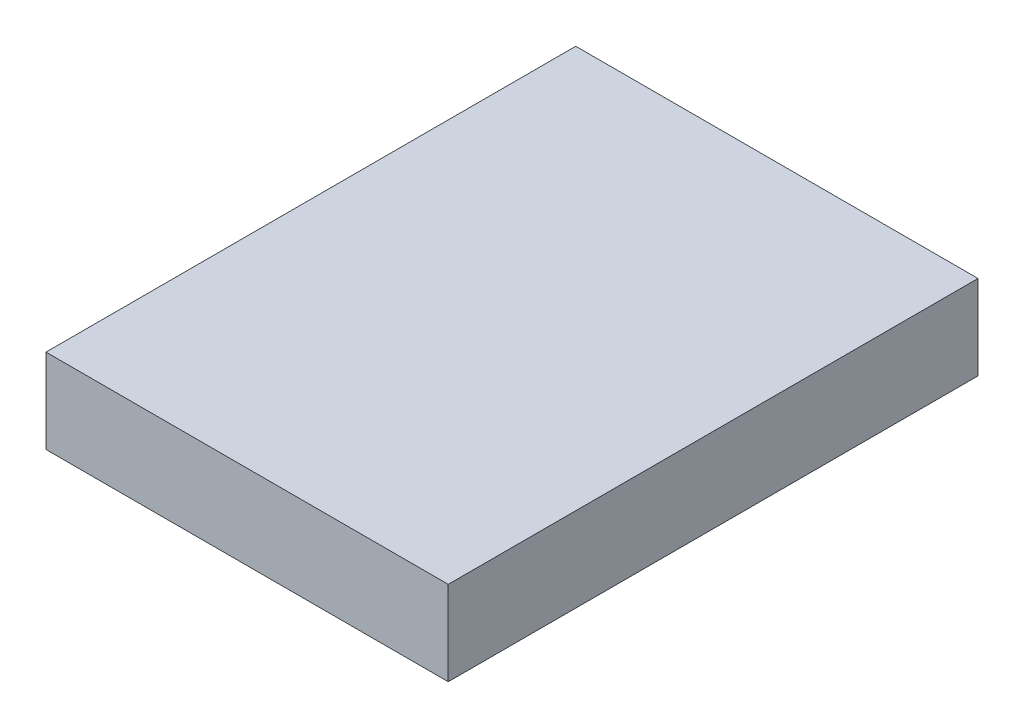
SolidWorks part; units mm, degrees
material "PBTP"
ref_plane "Front Plane" through (0, 0, 0) normal (0, 0, 1) x (1, 0, 0)
ref_plane "Top Plane" through (0, 0, 0) normal (0, 1, 0) x (1, 0, 0)
ref_plane "Right Plane" through (0, 0, 0) normal (1, 0, 0) x (0, 0, -1)
sketch "Sketch1" plane through (0, 0, 0) normal (0, 1, 0) x (1, 0, 0)
  line L1 (-10.25, -13.5) -> (10.25, -13.5)
  line L2 (-10.25, -13.5) -> (-10.25, 13.5)
  line L3 (-10.25, 13.5) -> (10.25, 13.5)
  line L4 (10.25, -13.5) -> (10.25, 13.5)
  line L5 (-10.25, -13.5) -> (10.25, 13.5) construction
  line L6 (-10.25, 13.5) -> (10.25, -13.5) construction
  point P0 (0, 0)
  dimension "D1" = 20.5
  dimension "D2" = 27
extrude "Boss-Extrude1" add sketch "Sketch1" along normal blind 4.3
